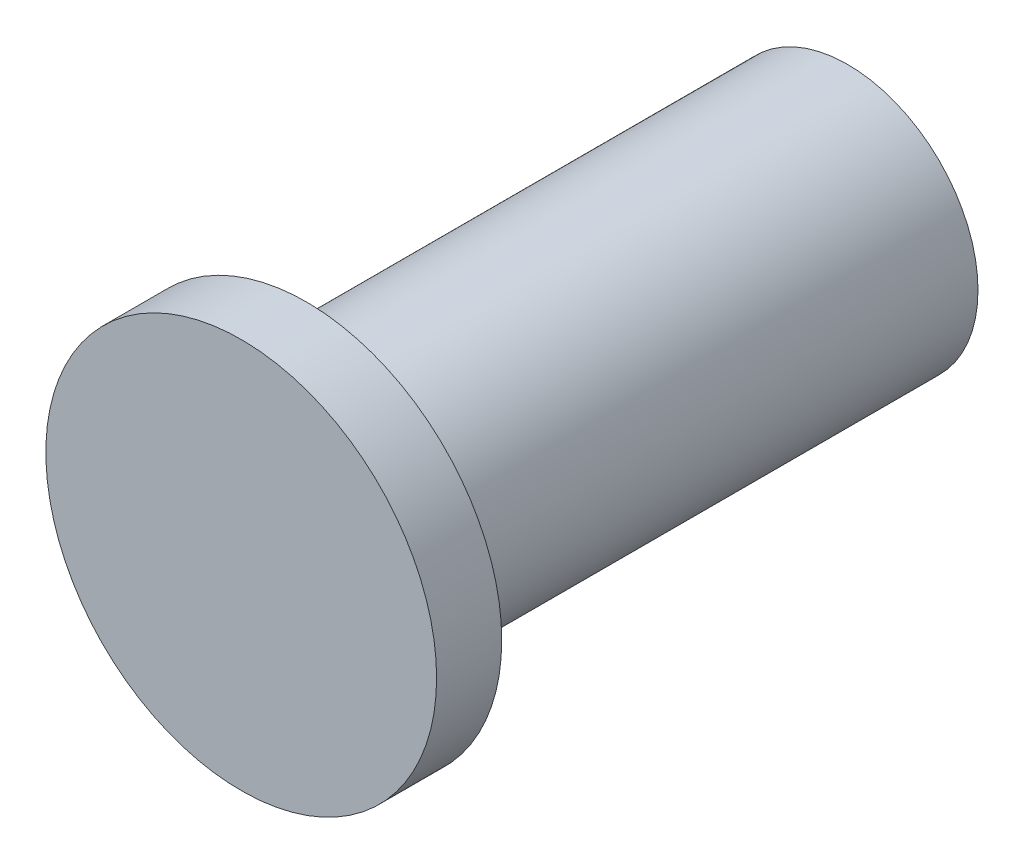
SolidWorks part; units mm, degrees
ref_plane "Front Plane" through (0, 0, 0) normal (0, 0, 1) x (1, 0, 0)
ref_plane "Top Plane" through (0, 0, 0) normal (0, 1, 0) x (1, 0, 0)
ref_plane "Right Plane" through (0, 0, 0) normal (1, 0, 0) x (0, 0, -1)
sketch "Sketch2" plane through (0, 0, 0) normal (0, 0, 1) x (1, 0, 0)
  circle A0 centre (0, 0) radius 4
  dimension "D1" = 8
extrude "Boss-Extrude4" add sketch "Sketch2" along normal blind 16 and the other way blind 0.6254
sketch "Sketch4" plane through (0, 0, 16) normal (0, 0, 1) x (1, 0, 0)
  circle A0 centre (0, 0) radius 6
extrude "Boss-Extrude5" add sketch "Sketch4" along normal blind 2
sketch "Sketch5" plane through (0, 0, -0.6254) normal (0, 0, -1) x (-1, 0, 0)
  circle A0 centre (0, 0) radius 3
extrude "Cut-Extrude1" cut sketch "Sketch5" against normal blind 16
